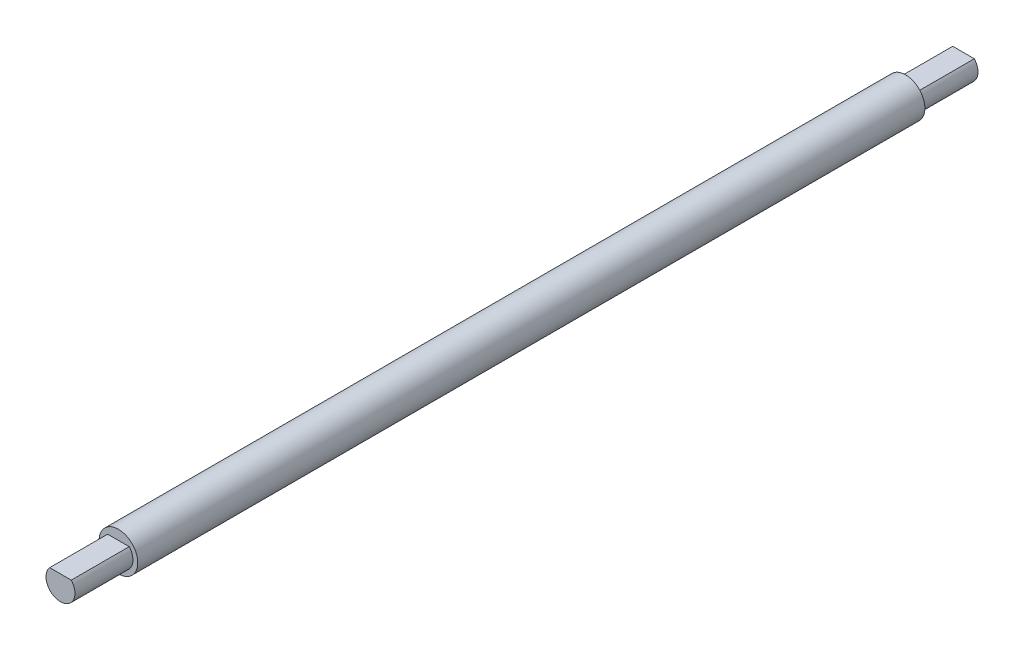
SolidWorks part; units mm, degrees
material "Barra Redonda SAE 1020 - 1/2\""
ref_plane "Plano frontal" through (0, 0, 0) normal (0, 0, 1) x (1, 0, 0)
ref_plane "Plano superior" through (0, 0, 0) normal (0, 1, 0) x (1, 0, 0)
ref_plane "Plano direito" through (0, 0, 0) normal (1, 0, 0) x (0, 0, -1)
sketch "Esboço1" plane through (0, 0, 0) normal (0, 0, 1) x (1, 0, 0)
  circle A0 centre (0, 0) radius 6.35
  dimension "D1" = 12.7
extrude "Ressalto-extrusão1" add sketch "Esboço1" along normal blind 187
sketch "Esboço2" plane through (0, 0, 187) normal (0, 0, 1) x (1, 0, 0)
  circle A0 centre (0, 0) radius 4
  circle A1 centre (0, 0) radius 12.7
  dimension "D1" = 8
  dimension "D2" = 25.4
extrude "Corte-extrusão1" cut sketch "Esboço2" against normal through all
sketch "Esboço3" plane through (0, 0, 0) normal (1, 0, 0) x (0, 0, -1)
  line L0 (-187, 4) -> (-187, -4) construction
  line L1 (-187, 2) -> (-175, 2)
  line L2 (-187, 2) -> (-187, 12)
  line L3 (-187, 12) -> (-175, 12)
  line L4 (-175, 2) -> (-175, 12)
  line L5 (-187, 0) -> (-121.987, 0) construction
  line L6 (0, -4) -> (0, 4) construction
  line L7 (0, 2) -> (-12, 2)
  line L8 (0, 2) -> (0, 12)
  line L9 (0, 12) -> (-12, 12)
  line L10 (-12, 2) -> (-12, 12)
  dimension "D1" = 12
  dimension "D2" = 10
  dimension "D3" = 2
  dimension "D4" = 12
  dimension "D5" = 10
  dimension "D6" = 2
extrude "Corte-extrusão2" cut sketch "Esboço3" against normal through all and the other way through all
sketch "Esboço5" plane through (0, 0, 0) normal (1, 0, 0) x (0, 0, -1)
  line L0 (0, 0) -> (-120.5536, 0) construction
  line L1 (0, -4) -> (0, 2) construction
  line L2 (-187, 2) -> (-187, -4) construction
  line L3 (-187, 3) -> (-175, 3)
  line L4 (-187, 3) -> (-187, 13)
  line L5 (-187, 13) -> (-175, 13)
  line L6 (0, 3) -> (-12, 3)
  line L7 (-175, 3) -> (-175, 13)
  line L8 (-175, 4) -> (-175, 2) construction
  line L9 (0, 3) -> (0, 13)
  line L10 (0, 13) -> (-12, 13)
  line L11 (-12, 3) -> (-12, 13)
  line L12 (-12, 2) -> (-12, 4) construction
  dimension "D1" = 10
  dimension "D2" = 6
  dimension "D3" = 10
  dimension "D4" = 6
revolve "Corte-Revolução2" cut sketch "Esboço5" angle 360 about L0
